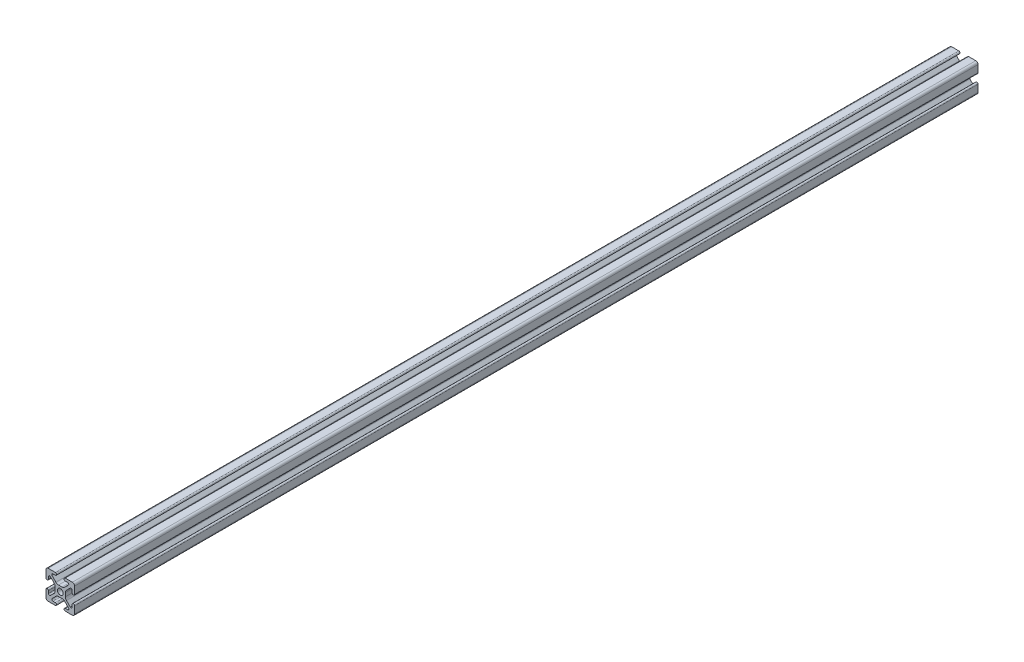
SolidWorks part; units mm, degrees
ref_plane "Front Plane" through (0, 0, 0) normal (0, 0, 1) x (1, 0, 0)
ref_plane "Top Plane" through (0, 0, 0) normal (0, 1, 0) x (1, 0, 0)
ref_plane "Right Plane" through (0, 0, 0) normal (1, 0, 0) x (0, 0, -1)
ref_plane "Plane1" through (0, 0, -25) normal (0, 0, -1) x (-1, 0, 0)
sketch "Sketch1" plane through (0, 0, -25) normal (0, 0, -1) x (-1, 0, 0)
  line L0 (12.5, 4.32) -> (12.5, 10.5371)
  line L1 (10.5371, 12.5) -> (4.32, 12.5)
  line L2 (4.32, 10.36) -> (6.42, 10.36)
  line L3 (7.1337, 8.6353) -> (3.7953, 5.3018)
  line L4 (1.5554, 4.375) -> (-1.5554, 4.375)
  line L5 (-3.7953, 5.3018) -> (-7.1337, 8.6353)
  line L6 (-6.42, 10.36) -> (-4.32, 10.36)
  line L7 (-4.32, 12.5) -> (-10.5371, 12.5)
  line L8 (-12.5, 10.5371) -> (-12.5, 4.32)
  line L9 (-10.36, 4.32) -> (-10.36, 6.3969)
  line L10 (-8.6363, 7.1116) -> (-5.4322, 3.9121)
  line L11 (-4.455, 1.5554) -> (-4.455, -1.5554)
  line L12 (-5.4322, -3.9121) -> (-8.6363, -7.1116)
  line L13 (-10.36, -6.3969) -> (-10.36, -4.32)
  line L14 (-12.5, -4.32) -> (-12.5, -10.5371)
  line L15 (-10.5371, -12.5) -> (-4.3879, -12.5)
  line L16 (-4.3879, -10.36) -> (-6.42, -10.36)
  line L17 (-7.1337, -8.6353) -> (-3.7953, -5.3018)
  line L18 (-1.5554, -4.375) -> (1.5554, -4.375)
  line L19 (3.7953, -5.3018) -> (7.1337, -8.6353)
  line L20 (6.42, -10.36) -> (4.3879, -10.36)
  line L21 (4.3879, -12.5) -> (10.5371, -12.5)
  line L22 (12.5, -10.5371) -> (12.5, -4.32)
  line L23 (10.36, -4.32) -> (10.36, -6.3969)
  line L24 (8.6363, -7.1116) -> (5.4322, -3.9121)
  line L25 (4.455, -1.5554) -> (4.455, 1.5554)
  line L26 (5.4322, 3.9121) -> (8.6363, 7.1116)
  line L27 (10.36, 6.3969) -> (10.36, 4.32)
  circle A0 centre (0, 0) radius 2.5
  arc A1 (12.5, 10.5371) -> (10.5371, 12.5) centre (10.5371, 10.5371) ccw
  arc A2 (4.32, 12.5) -> (4.32, 10.36) centre (4.32, 11.43) ccw
  arc A3 (6.42, 10.36) -> (7.1337, 8.6353) centre (6.42, 9.35) cw
  arc A4 (3.7953, 5.3018) -> (1.5554, 4.375) centre (1.5554, 7.545) cw
  arc A5 (-1.5554, 4.375) -> (-3.7953, 5.3018) centre (-1.5554, 7.545) cw
  arc A6 (-7.1337, 8.6353) -> (-6.42, 10.36) centre (-6.42, 9.35) cw
  arc A7 (-4.32, 10.36) -> (-4.32, 12.5) centre (-4.32, 11.43) ccw
  arc A8 (-10.5371, 12.5) -> (-12.5, 10.5371) centre (-10.5371, 10.5371) ccw
  arc A9 (-12.5, 4.32) -> (-10.36, 4.32) centre (-11.43, 4.32) ccw
  arc A10 (-10.36, 6.3969) -> (-8.6363, 7.1116) centre (-9.35, 6.3969) cw
  arc A11 (-5.4322, 3.9121) -> (-4.455, 1.5554) centre (-7.7855, 1.5554) cw
  arc A12 (-4.455, -1.5554) -> (-5.4322, -3.9121) centre (-7.7855, -1.5554) cw
  arc A13 (-8.6363, -7.1116) -> (-10.36, -6.3969) centre (-9.35, -6.3969) cw
  arc A14 (-10.36, -4.32) -> (-12.5, -4.32) centre (-11.43, -4.32) ccw
  arc A15 (-12.5, -10.5371) -> (-10.5371, -12.5) centre (-10.5371, -10.5371) ccw
  arc A16 (-4.3879, -12.5) -> (-4.3879, -10.36) centre (-4.3879, -11.43) ccw
  arc A17 (-6.42, -10.36) -> (-7.1337, -8.6353) centre (-6.42, -9.35) cw
  arc A18 (-3.7953, -5.3018) -> (-1.5554, -4.375) centre (-1.5554, -7.545) cw
  arc A19 (1.5554, -4.375) -> (3.7953, -5.3018) centre (1.5554, -7.545) cw
  arc A20 (7.1337, -8.6353) -> (6.42, -10.36) centre (6.42, -9.35) cw
  arc A21 (4.3879, -10.36) -> (4.3879, -12.5) centre (4.3879, -11.43) ccw
  arc A22 (10.5371, -12.5) -> (12.5, -10.5371) centre (10.5371, -10.5371) ccw
  arc A23 (12.5, -4.32) -> (10.36, -4.32) centre (11.43, -4.32) ccw
  arc A24 (10.36, -6.3969) -> (8.6363, -7.1116) centre (9.35, -6.3969) cw
  arc A25 (5.4322, -3.9121) -> (4.455, -1.5554) centre (7.7855, -1.5554) cw
  arc A26 (4.455, 1.5554) -> (5.4322, 3.9121) centre (7.7855, 1.5554) cw
  arc A27 (8.6363, 7.1116) -> (10.36, 6.3969) centre (9.35, 6.3969) cw
  arc A28 (10.36, 4.32) -> (12.5, 4.32) centre (11.43, 4.32) ccw
extrude "Boss-Extrude1" add sketch "Sketch1" against normal blind 790
